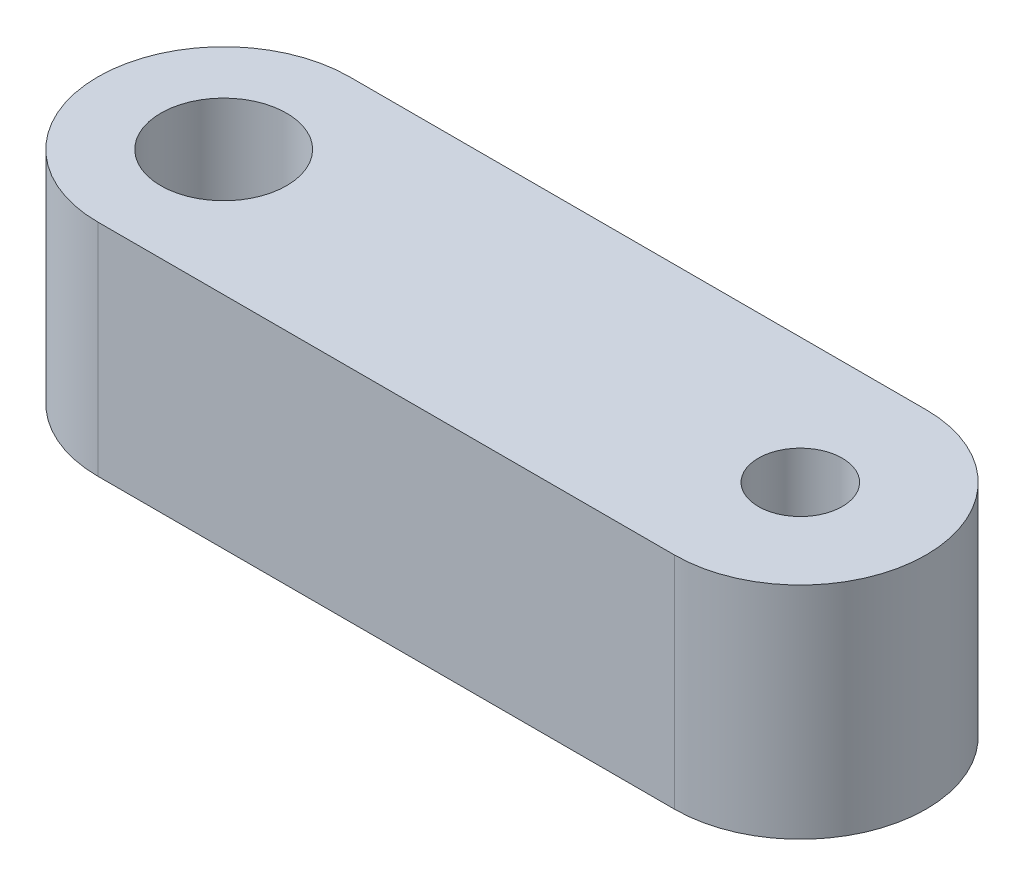
SolidWorks part; units mm, degrees
ref_plane "前视基准面" through (0, 0, 0) normal (0, 0, 1) x (1, 0, 0)
ref_plane "上视基准面" through (0, 0, 0) normal (0, 1, 0) x (1, 0, 0)
ref_plane "右视基准面" through (0, 0, 0) normal (1, 0, 0) x (0, 0, -1)
sketch "草图1" plane through (0, 0, 0) normal (0, 1, 0) x (1, 0, 0)
  line L0 (0, 0) -> (13.75, 0) construction
  line L1 (0, 3) -> (13.75, 3)
  line L2 (0, -3) -> (13.75, -3)
  arc A0 (0, 3) -> (0, -3) centre (0, 0) ccw
  arc A1 (13.75, -3) -> (13.75, 3) centre (13.75, 0) ccw
  point P3 (6.875, 0)
  dimension "D2" = 3
  dimension "D1" = 13.75
extrude "凸台-拉伸1" add sketch "草图1" along normal blind 5.25
sketch "草图2" plane through (0, 5.25, 0) normal (0, 1, 0) x (1, 0, 0)
  circle A0 centre (0, 0) radius 1.5
  circle A1 centre (13.75, 0) radius 1
  dimension "D1" = 2
  dimension "D2" = 3
extrude "切除-拉伸1" cut sketch "草图2" against normal up to next
